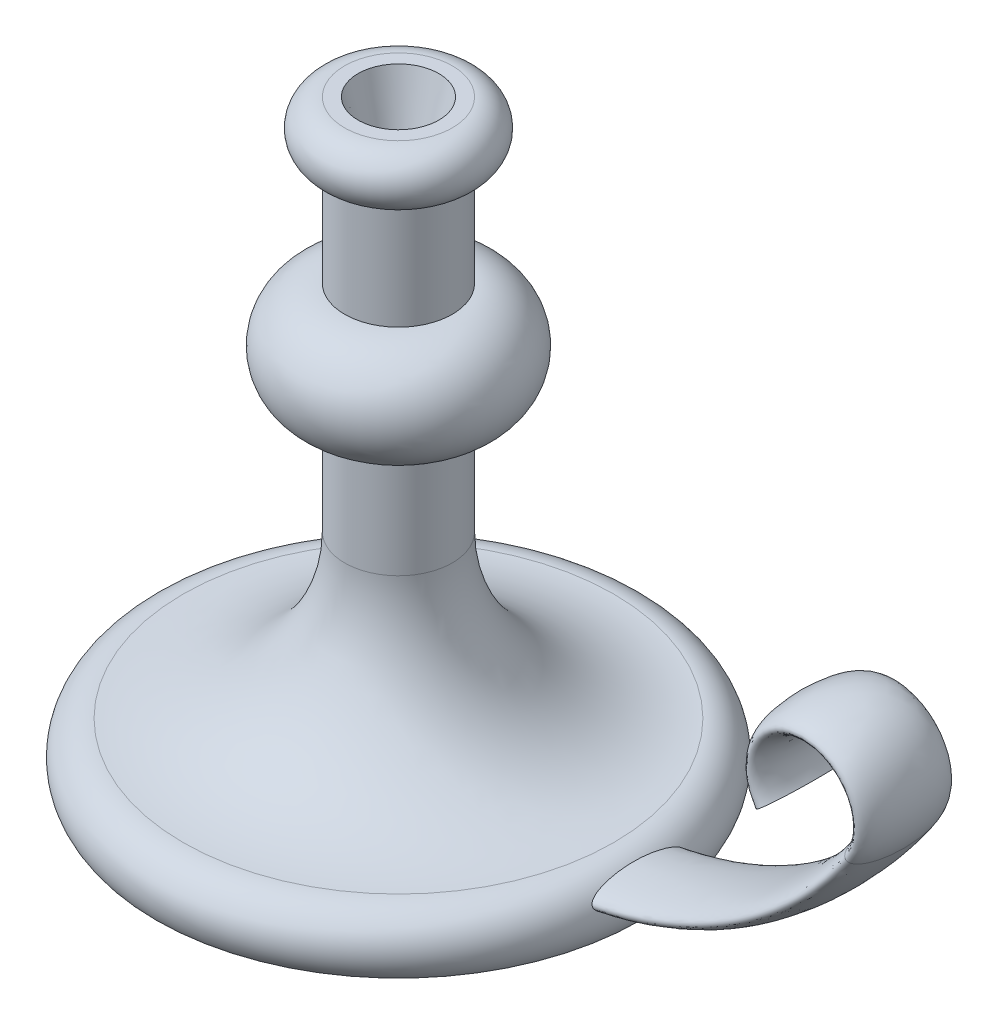
SolidWorks part; units mm, degrees
ref_plane "Front Plane" through (0, 0, 0) normal (0, 0, 1) x (1, 0, 0)
ref_plane "Top Plane" through (0, 0, 0) normal (0, 1, 0) x (1, 0, 0)
ref_plane "Right Plane" through (0, 0, 0) normal (1, 0, 0) x (0, 0, -1)
sketch "Sketch1" plane through (0, 0, 0) normal (0, 0, 1) x (1, 0, 0)
  line L0 (0, 220) -> (0, 0)
  line L1 (0, 0) -> (90, 0)
  line L2 (0, 220) -> (20, 220)
  line L3 (20, 200) -> (20, 160)
  line L4 (20, 120) -> (20, 80)
  arc A0 (20, 220) -> (20, 200) centre (20, 210) cw
  arc A1 (20, 160) -> (20, 120) centre (20, 140) cw
  arc A2 (20, 80) -> (80, 20) centre (80, 80) ccw
  arc A3 (80, 20) -> (90, 0) centre (80, 7.5) cw
  point P13 (91.1803, 13.0902)
  dimension "D4" = 10
  dimension "D5" = 20
  dimension "D7" = 40
  dimension "D8" = 60
  dimension "D1" = 20
  dimension "D2" = 220
  dimension "D3" = 90
  dimension "D6" = 40
  dimension "D9" = 12.5
revolve "Revolve1" add sketch "Sketch1" angle 360 about L0
sketch "Sketch2" plane through (0, 0, 0) normal (0, 0, 1) x (1, 0, 0)
  line L0 (0, 10) -> (60, 10)
  line L1 (0, 160) -> (0, 200) construction
  arc A0 (60, 10) -> (183.8035, 75) centre (60, 160.4024) ccw
  arc A1 (183.8035, 75) -> (150.8776, 75) centre (167.3405, 86.3565) ccw
  point P6 (0, 0)
  point P9 (0, 0)
  dimension "D2" = 150.4024
  dimension "D4" = 20
  dimension "D1" = 60
  dimension "D3" = 65
  dimension "D5" = 10
sketch "Sketch5" plane through (0, 220, 0) normal (0, 1, 0) x (1, 0, 0)
  circle A0 centre (0, 0) radius 15
  dimension "D1" = 30
extrude "Cut-Extrude1" cut sketch "Sketch5" against normal blind 25 draft 15
sketch "Sketch7" plane through (0, 0, 0) normal (1, 0, 0) x (0, 0, -1)
  ellipse E0 centre (0, 10) end of major axis (-17.5, 10) minor radius 5
  dimension "D1" = 35
  dimension "D2" = 10
sweep "Sweep1" add profiles "Sketch7" path "Sketch2"
